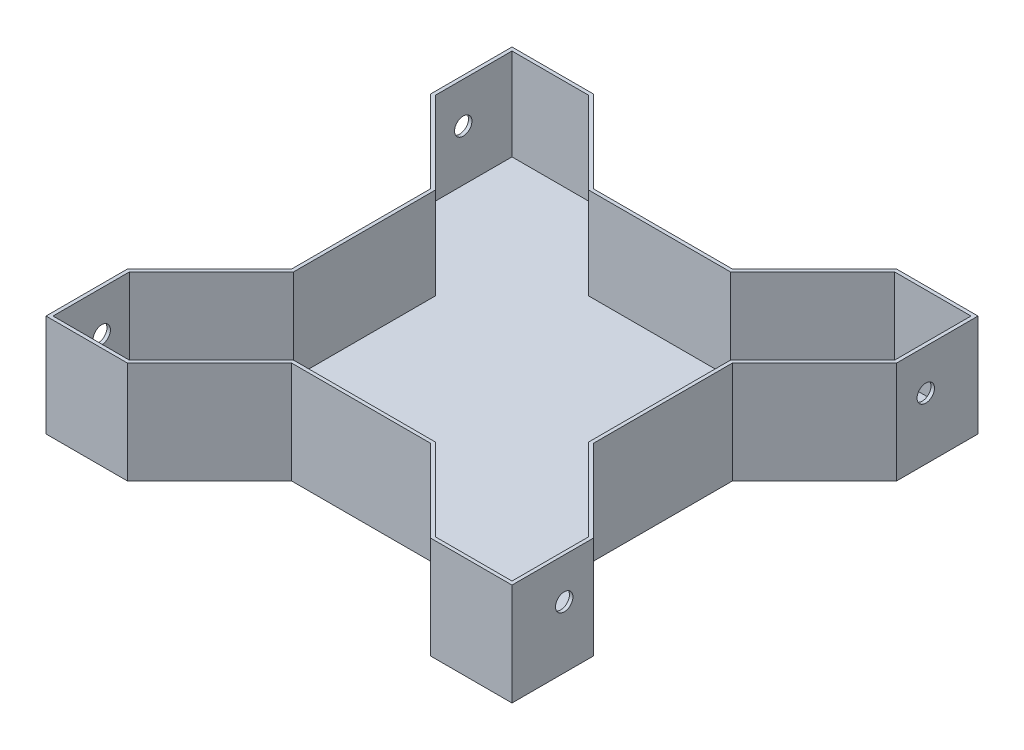
SolidWorks part; units mm, degrees
other "Markup1"
sketch "Sketch24" plane through (-161.6422, 88, 252.2031) normal (-0.9961, 0.087, 0.0135) x (-0.0555, -0.7403, 0.6699)
material "1023 Carbon Steel Sheet (SS)"
ref_plane "Front Plane" through (0, 0, 0) normal (0, 0, 1) x (1, 0, 0)
ref_plane "Top Plane" through (0, 0, 0) normal (0, 1, 0) x (1, 0, 0)
ref_plane "Right Plane" through (0, 0, 0) normal (1, 0, 0) x (0, 0, -1)
sketch "Sketch1" plane through (0, 0, 0) normal (0, 1, 0) x (1, 0, 0)
  line L0 (-161.6422, 149.2183) -> (-91.6422, 149.2183)
  line L1 (-91.6422, 149.2183) -> (-20.9315, 78.5076)
  line L2 (-20.9315, 78.5076) -> (99.0685, 78.5076)
  line L3 (99.0685, 78.5076) -> (169.7792, 149.2183)
  line L4 (169.7792, 149.2183) -> (239.7792, 149.2183)
  line L5 (239.7792, 149.2183) -> (239.7792, 79.2183)
  line L6 (239.7792, 79.2183) -> (169.0685, 8.5076)
  line L7 (169.0685, 8.5076) -> (169.0685, -111.4924)
  line L8 (169.0685, -111.4924) -> (239.7792, -182.2031)
  line L9 (239.7792, -182.2031) -> (239.7792, -252.2031)
  line L10 (239.7792, -252.2031) -> (169.7792, -252.2031)
  line L11 (169.7792, -252.2031) -> (99.0685, -181.4924)
  line L12 (99.0685, -181.4924) -> (-20.9315, -181.4924)
  line L13 (-20.9315, -181.4924) -> (-91.6422, -252.2031)
  line L14 (-91.6422, -252.2031) -> (-161.6422, -252.2031)
  line L15 (-161.6422, -252.2031) -> (-161.6422, -182.2031)
  line L16 (-161.6422, -182.2031) -> (-90.9315, -111.4924)
  line L17 (-90.9315, -111.4924) -> (-90.9315, 8.5076)
  line L18 (-90.9315, 8.5076) -> (-161.6422, 79.2183)
  line L19 (-161.6422, 79.2183) -> (-161.6422, 149.2183)
  dimension "D1" = 70
  dimension "D2" = 70
  dimension "D3" = 70
  dimension "D4" = 70
  dimension "D5" = 70
  dimension "D6" = 70
  dimension "D7" = 70
  dimension "D8" = 70
  dimension "D9" = 100
  dimension "D10" = 100
  dimension "D11" = 100
  dimension "D12" = 100
  dimension "D13" = 100
  dimension "D14" = 100
  dimension "D15" = 100
  dimension "D16" = 100
  dimension "D17" = 135
  dimension "D18" = 120
  dimension "D19" = 120
  dimension "D20" = 135
  dimension "D21" = 135
  dimension "D22" = 135
  dimension "D23" = 135
extrude "Boss-Extrude1" add sketch "Sketch1" along normal blind 88 contours L1 L2 L3 L4 L5 L6 L7 L8 L9 L10 L11 L12 L13 L14 L15 L16 L17 L18 L19 L0
sketch "Sketch3" plane through (0, 88, 0) normal (0, 1, 0) x (1, 0, 0)
  line L0 (-161.6422, 79.2183) -> (-161.6422, 149.2183) construction
  line L1 (-161.6422, 149.2183) -> (-91.6422, 149.2183) construction
  line L2 (-91.6422, 149.2183) -> (-20.9315, 78.5076) construction
  line L3 (239.7792, 149.2183) -> (239.7792, 79.2183) construction
  line L4 (-90.9315, 8.5076) -> (-161.6422, 79.2183) construction
  line L5 (169.7792, 149.2183) -> (239.7792, 149.2183) construction
  line L6 (-20.9315, 78.5076) -> (99.0685, 78.5076) construction
  line L7 (-90.9315, -111.4924) -> (-90.9315, 8.5076) construction
  line L8 (99.0685, 78.5076) -> (169.7792, 149.2183) construction
  line L9 (-158.6422, 146.2183) -> (-158.6422, 80.4609)
  line L10 (171.0218, 146.2183) -> (100.3112, 75.5076)
  line L11 (-158.6422, 80.4609) -> (-87.9315, 9.7503)
  line L12 (-87.9315, 9.7503) -> (-87.9315, -112.735)
  line L13 (-87.9315, -112.735) -> (-158.6422, -183.4457)
  line L14 (-158.6422, -183.4457) -> (-158.6422, -249.2031)
  line L15 (-158.6422, -249.2031) -> (-92.8848, -249.2031)
  line L16 (-92.8848, -249.2031) -> (-22.1741, -178.4924)
  line L17 (-22.1741, -178.4924) -> (100.3112, -178.4924)
  line L18 (100.3112, -178.4924) -> (171.0218, -249.2031)
  line L19 (171.0218, -249.2031) -> (236.7792, -249.2031)
  line L20 (236.7792, -249.2031) -> (236.7792, -183.4457)
  line L21 (236.7792, -183.4457) -> (166.0685, -112.735)
  line L22 (166.0685, -112.735) -> (166.0685, 9.7503)
  line L23 (166.0685, 9.7503) -> (236.7792, 80.4609)
  line L24 (236.7792, 80.4609) -> (236.7792, 146.2183)
  line L25 (236.7792, 146.2183) -> (171.0218, 146.2183)
  line L26 (100.3112, 75.5076) -> (-22.1741, 75.5076)
  line L27 (-22.1741, 75.5076) -> (-92.8848, 146.2183)
  line L28 (-92.8848, 146.2183) -> (-158.6422, 146.2183)
  point P0 (-158.6422, 146.2183)
  point P5 (-158.6422, 80.4609)
  point P6 (-87.9315, 9.7503)
  point P10 (236.7792, 146.2183)
  point P11 (171.0218, 146.2183)
  point P12 (100.3112, 75.5076)
  point P18 (166.0685, 9.7503)
  point P19 (236.7792, 80.4609)
  point P20 (166.0685, -112.735)
  point P21 (236.7792, -183.4457)
  point P22 (-22.1741, 75.5076)
  point P23 (-92.8848, 146.2183)
  point P26 (236.7792, -249.2031)
  point P28 (171.0218, -249.2031)
  point P30 (100.3112, -178.4924)
  point P32 (-92.8848, -249.2031)
  point P37 (-22.1741, -178.4924)
  point P38 (-87.9315, -112.735)
  point P39 (-158.6422, -183.4457)
  point P40 (-158.6422, -249.2031)
  dimension "D1" = 3
  dimension "D2" = 3
  dimension "D3" = 3
  dimension "D4" = 3
  dimension "D5" = 3
  dimension "D6" = 3
  dimension "D7" = 3
  dimension "D8" = 3
  dimension "D9" = 3
  dimension "D10" = 3
  dimension "D11" = 3
  dimension "D12" = 3
  dimension "D13" = 3
  dimension "D14" = 3
  dimension "D15" = 3
  dimension "D16" = 3
extrude "Cut-Extrude1" cut sketch "Sketch3" against normal blind 79
sketch "Sketch4" plane through (239.7792, 0, 0) normal (1, 0, 0) x (0, 0, -1)
  line L0 (-182.2031, 88) -> (-252.2031, 88) construction
  line L1 (-252.2031, 88) -> (-252.2031, 0) construction
  circle A0 centre (-207.2031, 53) radius 7.5
  dimension "D1" = 35
  dimension "D2" = 45
extrude "Cut-Extrude2" cut sketch "Sketch4" against normal blind 47
sketch "Sketch6" plane through (239.7792, 0, 0) normal (1, 0, 0) x (0, 0, -1)
  line L0 (149.2183, 88) -> (79.2183, 88) construction
  line L1 (149.2183, 88) -> (149.2183, 0) construction
  circle A0 centre (104.2183, 53) radius 7.5
  dimension "D1" = 35
  dimension "D2" = 45
extrude "Cut-Extrude4" cut sketch "Sketch6" against normal blind 47
sketch "Sketch7" plane through (-161.6422, 0, 0) normal (-1, 0, 0) x (0, 0, 1)
  line L2 (-79.2183, 0) -> (-149.2183, 0) construction
  line L3 (-149.2183, 88) -> (-149.2183, 0) construction
  circle A0 centre (-104.2183, 53) radius 7.5
  dimension "D1" = 53
  dimension "D2" = 45
extrude "Cut-Extrude5" cut sketch "Sketch7" against normal blind 47
sketch "Sketch8" plane through (-161.6422, 0, 0) normal (-1, 0, 0) x (0, 0, 1)
  line L2 (252.2031, 88) -> (182.2031, 88) construction
  line L3 (252.2031, 88) -> (252.2031, 0) construction
  circle A0 centre (207.2031, 53) radius 7.5
  dimension "D1" = 35
  dimension "D2" = 45
extrude "Cut-Extrude6" cut sketch "Sketch8" against normal blind 47
sketch "Sketch10" plane through (0, 9, 0) normal (0, 1, 0) x (1, 0, 0)
  line L0 (-158.6422, 126.2183) -> (-158.6422, 100.4609)
  line L1 (-158.6422, 126.2183) -> (-161.6422, 126.2183)
  line L2 (-161.6422, 126.2183) -> (-161.6422, 136.2183)
  line L3 (-158.6422, 136.2183) -> (-161.6422, 136.2183)
  line L4 (-158.6422, 90.4609) -> (-161.6422, 90.4609)
  line L5 (-161.6422, 100.4609) -> (-161.6422, 90.4609)
  line L6 (-158.6422, 100.4609) -> (-161.6422, 100.4609)
  line L7 (-158.6422, 90.4609) -> (-158.6422, 80.4609)
  line L8 (-20.9315, 78.5076) -> (99.0685, 78.5076) construction
  line L9 (181.0218, 146.2183) -> (181.0218, 149.2183)
  line L10 (191.0218, 149.2183) -> (181.0218, 149.2183)
  line L11 (191.0218, 146.2183) -> (191.0218, 149.2183)
  line L12 (236.7792, 90.4609) -> (239.7792, 90.4609)
  line L13 (239.7792, 100.4609) -> (239.7792, 90.4609)
  line L14 (236.7792, 100.4609) -> (239.7792, 100.4609)
  line L15 (236.7792, 126.2183) -> (239.7792, 126.2183)
  line L16 (239.7792, 126.2183) -> (239.7792, 136.2183)
  line L17 (236.7792, 136.2183) -> (239.7792, 136.2183)
  line L18 (216.7792, 146.2183) -> (216.7792, 149.2183)
  line L19 (226.7792, 146.2183) -> (226.7792, 149.2183)
  line L20 (216.7792, 149.2183) -> (226.7792, 149.2183)
  line L22 (-112.8848, 146.2183) -> (-112.8848, 149.2183)
  line L23 (-112.8848, 149.2183) -> (-102.8848, 149.2183)
  line L24 (-102.8848, 146.2183) -> (-102.8848, 149.2183)
  line L25 (-112.8848, 146.2183) -> (-138.6422, 146.2183)
  line L26 (-148.6422, 146.2183) -> (-148.6422, 149.2183)
  line L27 (-138.6422, 146.2183) -> (-138.6422, 149.2183)
  line L28 (-138.6422, 149.2183) -> (-148.6422, 149.2183)
  line L29 (-148.6422, 146.2183) -> (-158.6422, 146.2183)
  line L30 (-12.1741, 75.5076) -> (-12.1741, 78.5076)
  line L31 (-12.1741, 78.5076) -> (-2.1741, 78.5076)
  line L32 (-2.1741, 78.5076) -> (-2.1741, 75.5076)
  line L33 (39.0685, 78.5076) -> (39.0685, 67.3065) construction
  line L34 (80.3112, 78.5076) -> (80.3112, 75.5076)
  line L35 (90.3112, 78.5076) -> (80.3112, 78.5076)
  line L36 (90.3112, 75.5076) -> (90.3112, 78.5076)
  line L37 (-91.6422, 149.2183) -> (-20.9315, 78.5076) construction
  line L38 (-92.8848, 146.2183) -> (-86.7925, 152.3106) construction
  line L39 (-83.6924, 141.2686) -> (-85.8137, 139.1472)
  line L40 (-92.8848, 146.2183) -> (-158.6422, 146.2183)
  line L41 (-158.6422, 146.2183) -> (-158.6422, 80.4609)
  line L42 (-158.6422, 80.4609) -> (-87.9315, 9.7503)
  line L43 (-87.9315, 9.7503) -> (-87.9315, -112.735)
  line L44 (-87.9315, -112.735) -> (-158.6422, -183.4457)
  line L45 (-158.6422, -183.4457) -> (-158.6422, -249.2031)
  line L46 (-158.6422, -249.2031) -> (-92.8848, -249.2031)
  line L47 (-92.8848, -249.2031) -> (-22.1741, -178.4924)
  line L48 (-22.1741, -178.4924) -> (100.3112, -178.4924)
  line L49 (100.3112, -178.4924) -> (171.0218, -249.2031)
  line L50 (171.0218, -249.2031) -> (236.7792, -249.2031)
  line L51 (236.7792, -249.2031) -> (236.7792, -183.4457)
  line L52 (236.7792, -183.4457) -> (166.0685, -112.735)
  line L53 (166.0685, -112.735) -> (166.0685, 9.7503)
  line L54 (166.0685, 9.7503) -> (236.7792, 80.4609)
  line L55 (236.7792, 80.4609) -> (236.7792, 146.2183)
  line L56 (236.7792, 146.2183) -> (171.0218, 146.2183)
  line L57 (171.0218, 146.2183) -> (100.3112, 75.5076)
  line L58 (100.3112, 75.5076) -> (-22.1741, 75.5076)
  line L59 (-22.1741, 75.5076) -> (-92.8848, 146.2183)
  line L60 (-92.8848, 146.2183) -> (-102.8848, 146.2183)
  line L61 (-158.6422, 146.2183) -> (-158.6422, 136.2183)
  line L62 (-158.6422, 80.4609) -> (-151.5711, 73.3899)
  line L63 (-87.9315, 9.7503) -> (-87.9315, -0.2497)
  line L64 (-87.9315, -112.735) -> (-95.0026, -119.8061)
  line L65 (-158.6422, -183.4457) -> (-158.6422, -193.4457)
  line L66 (-158.6422, -249.2031) -> (-148.6422, -249.2031)
  line L67 (-92.8848, -249.2031) -> (-85.8137, -242.132)
  line L68 (-22.1741, -178.4924) -> (-12.1741, -178.4924)
  line L69 (100.3112, -178.4924) -> (107.3822, -185.5634)
  line L70 (171.0218, -249.2031) -> (181.0218, -249.2031)
  line L71 (236.7792, -249.2031) -> (236.7792, -239.2031)
  line L72 (236.7792, -183.4457) -> (229.7081, -176.3746)
  line L73 (166.0685, -112.735) -> (166.0685, -102.735)
  line L74 (166.0685, 9.7503) -> (173.1396, 16.8213)
  line L75 (236.7792, 80.4609) -> (236.7792, 90.4609)
  line L76 (236.7792, 146.2183) -> (226.7792, 146.2183)
  line L77 (171.0218, 146.2183) -> (163.9508, 139.1472)
  line L78 (100.3112, 75.5076) -> (90.3112, 75.5076)
  line L79 (-22.1741, 75.5076) -> (-29.2452, 82.5787)
  line L80 (-83.6924, 141.2686) -> (-76.6213, 134.1975)
  line L81 (-76.6213, 134.1975) -> (-78.7427, 132.0762)
  line L82 (105.2609, 84.7) -> (107.3822, 82.5787)
  line L83 (-34.1949, 91.7711) -> (-36.3163, 89.6498)
  line L84 (-27.1239, 84.7) -> (-34.1949, 91.7711)
  line L85 (-27.1239, 84.7) -> (-29.2452, 82.5787)
  line L86 (105.2609, 84.7) -> (112.332, 91.7711)
  line L87 (112.332, 91.7711) -> (114.4533, 89.6498)
  line L88 (161.8294, 141.2686) -> (163.9508, 139.1472)
  line L89 (161.8294, 141.2686) -> (154.7584, 134.1975)
  line L90 (154.7584, 134.1975) -> (156.8797, 132.0762)
  line L91 (-161.6422, 149.2183) -> (-158.6422, 146.2183) construction
  line L92 (-97.1239, 14.7) -> (-95.0026, 16.8213)
  line L93 (-97.1239, 14.7) -> (-104.1949, 21.7711)
  line L94 (-104.1949, 21.7711) -> (-102.0736, 23.8924)
  line L95 (-146.6213, 64.1975) -> (-144.5, 66.3188)
  line L96 (-153.6924, 71.2686) -> (-146.6213, 64.1975)
  line L97 (-153.6924, 71.2686) -> (-151.5711, 73.3899)
  line L98 (239.7792, 149.2183) -> (236.7792, 146.2183) construction
  line L99 (182.332, 21.7711) -> (180.2106, 23.8924)
  line L100 (175.2609, 14.7) -> (182.332, 21.7711)
  line L101 (175.2609, 14.7) -> (173.1396, 16.8213)
  line L102 (224.7584, 64.1975) -> (222.6371, 66.3188)
  line L103 (231.8294, 71.2686) -> (229.7081, 73.3899)
  line L104 (231.8294, 71.2686) -> (224.7584, 64.1975)
  line L105 (-90.9315, -111.4924) -> (-90.9315, 8.5076) construction
  line L106 (-87.9315, -0.2497) -> (-90.9315, -0.2497)
  line L107 (-90.9315, -0.2497) -> (-90.9315, -10.2497)
  line L108 (-90.9315, -10.2497) -> (-87.9315, -10.2497)
  line L109 (169.0685, -10.2497) -> (166.0685, -10.2497)
  line L110 (166.0685, -0.2497) -> (169.0685, -0.2497)
  line L111 (169.0685, -0.2497) -> (169.0685, -10.2497)
  line L112 (-87.9315, -10.2497) -> (-87.9315, -92.735)
  line L113 (-95.0026, 16.8213) -> (-87.9315, 9.7503)
  line L114 (-144.5, 66.3188) -> (-102.0736, 23.8924)
  line L115 (-85.8137, 139.1472) -> (-92.8848, 146.2183)
  line L116 (-36.3163, 89.6498) -> (-78.7427, 132.0762)
  line L117 (-12.1741, 75.5076) -> (-22.1741, 75.5076)
  line L118 (80.3112, 75.5076) -> (-2.1741, 75.5076)
  line L119 (107.3822, 82.5787) -> (100.3112, 75.5076)
  line L120 (156.8797, 132.0762) -> (114.4533, 89.6498)
  line L121 (181.0218, 146.2183) -> (171.0218, 146.2183)
  line L122 (216.7792, 146.2183) -> (191.0218, 146.2183)
  line L123 (236.7792, 136.2183) -> (236.7792, 146.2183)
  line L124 (236.7792, 100.4609) -> (236.7792, 126.2183)
  line L125 (229.7081, 73.3899) -> (236.7792, 80.4609)
  line L126 (180.2106, 23.8924) -> (222.6371, 66.3188)
  line L127 (166.0685, -0.2497) -> (166.0685, 9.7503)
  line L128 (-90.9315, -51.4924) -> (224.7584, -51.4924) construction
  line L129 (166.0685, -92.735) -> (166.0685, -10.2497)
  line L130 (-83.6924, 141.2686) -> (-85.8137, 139.1472)
  line L131 (-83.6924, 141.2686) -> (-76.6213, 134.1975)
  line L132 (-76.6213, 134.1975) -> (-78.7427, 132.0762)
  line L133 (-161.6422, 126.2183) -> (-161.6422, 136.2183)
  line L134 (-158.6422, 126.2183) -> (-161.6422, 126.2183)
  line L135 (-158.6422, 136.2183) -> (-161.6422, 136.2183)
  line L136 (-112.8848, 146.2183) -> (-112.8848, 149.2183)
  line L137 (-76.6213, -237.1822) -> (-78.7427, -235.0609)
  line L138 (-83.6924, -244.2533) -> (-76.6213, -237.1822)
  line L139 (-83.6924, -244.2533) -> (-85.8137, -242.132)
  line L140 (-102.8848, -249.2031) -> (-102.8848, -252.2031)
  line L141 (-112.8848, -252.2031) -> (-102.8848, -252.2031)
  line L142 (-112.8848, -249.2031) -> (-112.8848, -252.2031)
  line L143 (-112.8848, 149.2183) -> (-102.8848, 149.2183)
  line L144 (-102.8848, 146.2183) -> (-102.8848, 149.2183)
  line L145 (-148.6422, 146.2183) -> (-148.6422, 149.2183)
  line L146 (-138.6422, 149.2183) -> (-148.6422, 149.2183)
  line L147 (-138.6422, 146.2183) -> (-138.6422, 149.2183)
  line L148 (-158.6422, 126.2183) -> (-161.6422, 126.2183)
  line L149 (-161.6422, 126.2183) -> (-161.6422, 136.2183)
  line L150 (-158.6422, 136.2183) -> (-161.6422, 136.2183)
  line L151 (-148.6422, 146.2183) -> (-148.6422, 149.2183)
  line L152 (-138.6422, 146.2183) -> (-138.6422, 149.2183)
  line L153 (-138.6422, 149.2183) -> (-148.6422, 149.2183)
  line L154 (-83.6924, 141.2686) -> (-85.8137, 139.1472)
  line L155 (-83.6924, 141.2686) -> (-76.6213, 134.1975)
  line L156 (-76.6213, 134.1975) -> (-78.7427, 132.0762)
  line L157 (-161.6422, 126.2183) -> (-161.6422, 136.2183)
  line L158 (-158.6422, 126.2183) -> (-161.6422, 126.2183)
  line L159 (-158.6422, 136.2183) -> (-161.6422, 136.2183)
  line L160 (-112.8848, 146.2183) -> (-112.8848, 149.2183)
  line L161 (-112.8848, 149.2183) -> (-102.8848, 149.2183)
  line L162 (-102.8848, 146.2183) -> (-102.8848, 149.2183)
  line L163 (-148.6422, 146.2183) -> (-148.6422, 149.2183)
  line L164 (-138.6422, 149.2183) -> (-148.6422, 149.2183)
  line L165 (-138.6422, 146.2183) -> (-138.6422, 149.2183)
  line L166 (-148.6422, -249.2031) -> (-148.6422, -252.2031)
  line L167 (-138.6422, -249.2031) -> (-138.6422, -252.2031)
  line L168 (-138.6422, -252.2031) -> (-148.6422, -252.2031)
  line L169 (-158.6422, -239.2031) -> (-161.6422, -239.2031)
  line L170 (-158.6422, -229.2031) -> (-161.6422, -229.2031)
  line L171 (-161.6422, -229.2031) -> (-161.6422, -239.2031)
  line L172 (-158.6422, -239.2031) -> (-161.6422, -239.2031)
  line L173 (-161.6422, -229.2031) -> (-161.6422, -239.2031)
  line L174 (-158.6422, -229.2031) -> (-161.6422, -229.2031)
  line L175 (-158.6422, -239.2031) -> (-161.6422, -239.2031)
  line L176 (-158.6422, -229.2031) -> (-161.6422, -229.2031)
  line L177 (-161.6422, -229.2031) -> (-161.6422, -239.2031)
  line L178 (-153.6924, -174.2533) -> (-151.5711, -176.3746)
  line L179 (-153.6924, -174.2533) -> (-146.6213, -167.1822)
  line L180 (-146.6213, -167.1822) -> (-144.5, -169.3036)
  line L181 (-158.6422, -203.4457) -> (-161.6422, -203.4457)
  line L182 (-161.6422, -203.4457) -> (-161.6422, -193.4457)
  line L183 (-158.6422, -193.4457) -> (-161.6422, -193.4457)
  line L184 (-158.6422, -239.2031) -> (-161.6422, -239.2031)
  line L185 (-161.6422, -229.2031) -> (-161.6422, -239.2031)
  line L186 (-158.6422, -229.2031) -> (-161.6422, -229.2031)
  line L187 (-90.9315, -92.735) -> (-87.9315, -92.735)
  line L188 (-90.9315, -102.735) -> (-90.9315, -92.735)
  line L189 (-87.9315, -102.735) -> (-90.9315, -102.735)
  line L190 (-97.1239, -117.6848) -> (-95.0026, -119.8061)
  line L191 (-97.1239, -117.6848) -> (-104.1949, -124.7558)
  line L192 (-12.1741, -178.4924) -> (-12.1741, -181.4924)
  line L193 (-12.1741, -181.4924) -> (-2.1741, -181.4924)
  line L194 (239.7792, -252.2031) -> (236.7792, -249.2031) construction
  line L195 (39.0685, -181.4924) -> (39.0685, -170.2913) construction
  line L196 (169.0685, -102.735) -> (169.0685, -92.735)
  line L197 (166.0685, -102.735) -> (169.0685, -102.735)
  line L198 (169.0685, -92.735) -> (166.0685, -92.735)
  line L199 (231.8294, -174.2533) -> (224.7584, -167.1822)
  line L200 (231.8294, -174.2533) -> (229.7081, -176.3746)
  line L201 (224.7584, -167.1822) -> (222.6371, -169.3036)
  line L202 (175.2609, -117.6848) -> (173.1396, -119.8061)
  line L203 (175.2609, -117.6848) -> (182.332, -124.7558)
  line L204 (182.332, -124.7558) -> (180.2106, -126.8771)
  line L205 (154.7584, -237.1822) -> (156.8797, -235.0609)
  line L206 (161.8294, -244.2533) -> (154.7584, -237.1822)
  line L207 (161.8294, -244.2533) -> (163.9508, -242.132)
  line L208 (112.332, -194.7558) -> (114.4533, -192.6345)
  line L209 (105.2609, -187.6848) -> (112.332, -194.7558)
  line L210 (105.2609, -187.6848) -> (107.3822, -185.5634)
  line L211 (90.3112, -178.4924) -> (90.3112, -181.4924)
  line L212 (90.3112, -181.4924) -> (80.3112, -181.4924)
  line L213 (80.3112, -181.4924) -> (80.3112, -178.4924)
  line L214 (-2.1741, -181.4924) -> (-2.1741, -178.4924)
  line L215 (216.7792, -252.2031) -> (226.7792, -252.2031)
  line L216 (226.7792, -249.2031) -> (226.7792, -252.2031)
  line L217 (216.7792, -249.2031) -> (216.7792, -252.2031)
  line L218 (236.7792, -239.2031) -> (239.7792, -239.2031)
  line L219 (239.7792, -229.2031) -> (239.7792, -239.2031)
  line L220 (236.7792, -229.2031) -> (239.7792, -229.2031)
  line L221 (236.7792, -203.4457) -> (239.7792, -203.4457)
  line L222 (239.7792, -203.4457) -> (239.7792, -193.4457)
  line L223 (236.7792, -193.4457) -> (239.7792, -193.4457)
  line L224 (191.0218, -249.2031) -> (191.0218, -252.2031)
  line L225 (191.0218, -252.2031) -> (181.0218, -252.2031)
  line L226 (181.0218, -249.2031) -> (181.0218, -252.2031)
  line L227 (-87.9315, -102.735) -> (-87.9315, -112.735)
  line L228 (-151.5711, -176.3746) -> (-158.6422, -183.4457)
  line L229 (-158.6422, -203.4457) -> (-158.6422, -249.2031)
  line L230 (-138.6422, -249.2031) -> (-112.8848, -249.2031)
  line L231 (-102.8848, -249.2031) -> (-92.8848, -249.2031)
  line L232 (-78.7427, -235.0609) -> (-22.1741, -178.4924)
  line L233 (-2.1741, -178.4924) -> (80.3112, -178.4924)
  line L234 (90.3112, -178.4924) -> (100.3112, -178.4924)
  line L235 (114.4533, -192.6345) -> (156.8797, -235.0609)
  line L236 (163.9508, -242.132) -> (171.0218, -249.2031)
  line L237 (191.0218, -249.2031) -> (216.7792, -249.2031)
  line L238 (226.7792, -249.2031) -> (236.7792, -249.2031)
  line L239 (236.7792, -229.2031) -> (236.7792, -203.4457)
  line L240 (236.7792, -193.4457) -> (236.7792, -183.4457)
  line L241 (222.6371, -169.3036) -> (180.2106, -126.8771)
  line L242 (173.1396, -119.8061) -> (166.0685, -112.735)
  line L243 (-104.1949, -124.7558) -> (-102.0736, -126.8771)
  line L244 (-102.0736, -126.8771) -> (-144.5, -169.3036)
  point P7 (-12.1741, 78.5076)
  point P48 (226.7792, 147.7183)
  point P68 (-83.6924, 141.2686)
  point P107 (-90.9315, -0.2497)
  point P150 (-102.0736, -126.8771)
  point P199 (226.7792, -250.7031)
  dimension "D2" = 3
  dimension "D3" = 10
  dimension "D4" = 10
  dimension "D5" = 10
  dimension "D6" = 10
  dimension "D7" = 10
  dimension "D8" = 10
  dimension "D9" = 10
  dimension "D10" = 10
  dimension "D1" = 0
sketch "Sketch11" plane through (0, 0, -78.5076) normal (0, 0, -1) x (-1, 0, 0)
  line L0 (-90.3112, 9) -> (-90.3112, 10.5)
  line L1 (-90.3112, 9) -> (-100.3112, 9) construction
  line L2 (-90.3112, 10.5) -> (-80.3112, 10.5)
  line L3 (-80.3112, 10.5) -> (-80.3112, 9)
  line L4 (-99.0685, 0) -> (20.9315, 0)
  line L5 (20.9315, 0) -> (20.9315, 88)
  line L6 (20.9315, 88) -> (-99.0685, 88)
  line L7 (-99.0685, 88) -> (-99.0685, 0)
  line L8 (-99.0685, 0) -> (20.9315, 0)
  line L9 (20.9315, 0) -> (20.9315, 88)
  line L10 (20.9315, 88) -> (-99.0685, 88)
  line L11 (-99.0685, 88) -> (-99.0685, 0)
  line L12 (2.1741, 9) -> (-80.3112, 9) construction
  line L13 (-80.3112, 9) -> (-80.3112, 7.5)
  line L14 (-80.3112, 7.5) -> (-90.3112, 7.5)
  line L15 (-90.3112, 7.5) -> (-90.3112, 9)
  line L16 (-39.0685, 9) -> (-39.0685, 30.0924) construction
  line L17 (12.1741, 7.5) -> (12.1741, 9)
  line L18 (2.1741, 7.5) -> (12.1741, 7.5)
  line L19 (2.1741, 9) -> (2.1741, 7.5)
  line L20 (2.1741, 10.5) -> (2.1741, 9)
  line L21 (12.1741, 10.5) -> (2.1741, 10.5)
  line L22 (12.1741, 9) -> (12.1741, 10.5)
  dimension "D2" = 10
  dimension "D3" = 10
  dimension "D4" = 1.5
  dimension "D5" = 1.5
  dimension "D1" = 0
sketch "Sketch12" plane through (10.2804, 0, 10.2804) normal (-0.7071, 0, -0.7071) x (-0.7071, 0, 0.7071)
  line L0 (-214.3227, 9) -> (-214.3227, 10.5)
  line L1 (-214.3227, 9) -> (-204.3227, 9) construction
  line L2 (-214.3227, 9) -> (-224.3227, 9) construction
  line L3 (-214.3227, 10.5) -> (-204.3227, 10.5)
  line L4 (-225.5653, 0) -> (-125.5653, 0)
  line L5 (-125.5653, 0) -> (-125.5653, 88)
  line L6 (-125.5653, 88) -> (-225.5653, 88)
  line L7 (-225.5653, 88) -> (-225.5653, 0)
  line L8 (-225.5653, 0) -> (-125.5653, 0)
  line L9 (-125.5653, 0) -> (-125.5653, 88)
  line L10 (-125.5653, 88) -> (-225.5653, 88)
  line L11 (-225.5653, 88) -> (-225.5653, 0)
  line L12 (-204.3227, 10.5) -> (-204.3227, 9)
  line L13 (-204.3227, 9) -> (-204.3227, 7.5)
  line L14 (-204.3227, 7.5) -> (-214.3227, 7.5)
  line L15 (-214.3227, 7.5) -> (-214.3227, 9)
  line L16 (-174.3227, 9) -> (-174.3227, 17.0419) construction
  line L17 (-144.3227, 9) -> (-204.3227, 9) construction
  line L18 (-134.3227, 7.5) -> (-134.3227, 9)
  line L19 (-144.3227, 7.5) -> (-134.3227, 7.5)
  line L20 (-144.3227, 9) -> (-144.3227, 7.5)
  line L21 (-144.3227, 10.5) -> (-144.3227, 9)
  line L22 (-134.3227, 10.5) -> (-144.3227, 10.5)
  line L23 (-134.3227, 9) -> (-134.3227, 10.5)
  dimension "D2" = 10
  dimension "D3" = 1.5
  dimension "D4" = 1.5
  dimension "D1" = 0
sketch "Sketch13" plane through (0, 0, -149.2183) normal (0, 0, -1) x (-1, 0, 0)
  line L0 (-226.7792, 9) -> (-226.7792, 10.5)
  line L1 (-226.7792, 10.5) -> (-216.7792, 10.5)
  line L2 (-216.7792, 10.5) -> (-216.7792, 9)
  line L3 (-216.7792, 9) -> (-216.7792, 7.5)
  line L4 (-239.7792, 0) -> (-169.7792, 0)
  line L5 (-169.7792, 0) -> (-169.7792, 88)
  line L6 (-169.7792, 88) -> (-239.7792, 88)
  line L7 (-239.7792, 88) -> (-239.7792, 0)
  line L8 (-239.7792, 0) -> (-169.7792, 0)
  line L9 (-169.7792, 0) -> (-169.7792, 88)
  line L10 (-169.7792, 88) -> (-239.7792, 88)
  line L11 (-239.7792, 88) -> (-239.7792, 0)
  line L12 (-216.7792, 7.5) -> (-226.7792, 7.5)
  line L13 (-226.7792, 7.5) -> (-226.7792, 9)
  line L14 (-201.4239, 9) -> (-201.4239, 19.1162) construction
  line L15 (-222.6371, 9) -> (-180.2106, 9) construction
  line L16 (-191.0218, 9) -> (-191.0218, 10.5)
  line L17 (-191.0218, 10.5) -> (-181.0218, 10.5)
  line L18 (-181.0218, 10.5) -> (-181.0218, 9)
  line L19 (-181.0218, 9) -> (-181.0218, 7.5)
  line L20 (-181.0218, 7.5) -> (-191.0218, 7.5)
  line L21 (-191.0218, 7.5) -> (-191.0218, 9)
  dimension "D2" = 10
  dimension "D3" = 1.5
  dimension "D4" = 1.5
  dimension "D5" = 10
  dimension "D6" = 1.5
  dimension "D7" = 1.5
  dimension "D1" = 0
sketch "Sketch14" plane through (239.7792, 0, 0) normal (1, 0, 0) x (0, 0, -1)
  line L0 (100.4609, 9) -> (100.4609, 7.5)
  line L1 (100.4609, 7.5) -> (90.222, 7.5)
  line L2 (90.222, 7.5) -> (90.4609, 9)
  line L3 (90.4609, 9) -> (90.4609, 10.5)
  line L4 (79.2183, 0) -> (149.2183, 0)
  line L5 (149.2183, 0) -> (149.2183, 88)
  line L6 (149.2183, 88) -> (79.2183, 88)
  line L7 (79.2183, 88) -> (79.2183, 0)
  line L8 (79.2183, 0) -> (149.2183, 0)
  line L9 (149.2183, 0) -> (149.2183, 88)
  line L10 (149.2183, 88) -> (79.2183, 88)
  line L11 (79.2183, 88) -> (79.2183, 0)
  line L12 (90.4609, 10.5) -> (100.4609, 10.5)
  line L13 (100.4609, 10.5) -> (100.4609, 9)
  line L14 (126.2183, 9) -> (126.2183, 10.5)
  line L15 (126.2183, 10.5) -> (136.2183, 10.5)
  line L16 (136.2183, 10.5) -> (136.2183, 9)
  line L17 (136.2183, 9) -> (136.2183, 7.5)
  line L18 (136.2183, 7.5) -> (126.2183, 7.5)
  line L19 (126.2183, 7.5) -> (126.2183, 9)
  dimension "D2" = 1.5
  dimension "D3" = 1.5
  dimension "D4" = 10
  dimension "D5" = 1.5
  dimension "D6" = 1.5
  dimension "D1" = 0
sketch "Sketch16" plane through (0, 9, 0) normal (0, 1, 0) x (1, 0, 0)
  line L20 (-92.8848, 146.2183) -> (-158.6422, 146.2183)
  line L21 (-158.6422, 146.2183) -> (-158.6422, 80.4609)
  line L22 (-158.6422, 80.4609) -> (-87.9315, 9.7503)
  line L23 (-87.9315, 9.7503) -> (-87.9315, -112.735)
  line L24 (-87.9315, -112.735) -> (-158.6422, -183.4457)
  line L25 (-158.6422, -183.4457) -> (-158.6422, -249.2031)
  line L26 (-158.6422, -249.2031) -> (-92.8848, -249.2031)
  line L27 (-92.8848, -249.2031) -> (-22.1741, -178.4924)
  line L28 (-22.1741, -178.4924) -> (100.3112, -178.4924)
  line L29 (100.3112, -178.4924) -> (171.0218, -249.2031)
  line L30 (171.0218, -249.2031) -> (236.7792, -249.2031)
  line L31 (236.7792, -249.2031) -> (236.7792, -183.4457)
  line L32 (236.7792, -183.4457) -> (166.0685, -112.735)
  line L33 (166.0685, -112.735) -> (166.0685, 9.7503)
  line L34 (166.0685, 9.7503) -> (236.7792, 80.4609)
  line L35 (236.7792, 80.4609) -> (236.7792, 146.2183)
  line L36 (236.7792, 146.2183) -> (171.0218, 146.2183)
  line L37 (171.0218, 146.2183) -> (100.3112, 75.5076)
  line L38 (100.3112, 75.5076) -> (-22.1741, 75.5076)
  line L39 (-22.1741, 75.5076) -> (-92.8848, 146.2183)
  line L40 (-92.8848, 146.2183) -> (-158.6422, 146.2183)
  line L41 (-158.6422, 146.2183) -> (-158.6422, 80.4609)
  line L42 (-158.6422, 80.4609) -> (-87.9315, 9.7503)
  line L43 (-87.9315, 9.7503) -> (-87.9315, -112.735)
  line L44 (-87.9315, -112.735) -> (-158.6422, -183.4457)
  line L45 (-158.6422, -183.4457) -> (-158.6422, -249.2031)
  line L46 (-158.6422, -249.2031) -> (-92.8848, -249.2031)
  line L47 (-92.8848, -249.2031) -> (-22.1741, -178.4924)
  line L48 (-22.1741, -178.4924) -> (100.3112, -178.4924)
  line L49 (100.3112, -178.4924) -> (171.0218, -249.2031)
  line L50 (171.0218, -249.2031) -> (236.7792, -249.2031)
  line L51 (236.7792, -249.2031) -> (236.7792, -183.4457)
  line L52 (236.7792, -183.4457) -> (166.0685, -112.735)
  line L53 (166.0685, -112.735) -> (166.0685, 9.7503)
  line L54 (166.0685, 9.7503) -> (236.7792, 80.4609)
  line L55 (236.7792, 80.4609) -> (236.7792, 146.2183)
  line L56 (236.7792, 146.2183) -> (171.0218, 146.2183)
  line L57 (171.0218, 146.2183) -> (100.3112, 75.5076)
  line L58 (100.3112, 75.5076) -> (-22.1741, 75.5076)
  line L59 (-22.1741, 75.5076) -> (-92.8848, 146.2183)
  dimension "D1" = 0
sketch "Sketch17" plane through (0, 0, 0) normal (0, -1, 0) x (1, 0, 0)
  line L20 (100.3112, -75.5076) -> (171.0218, -146.2183)
  line L21 (-22.1741, -75.5076) -> (100.3112, -75.5076)
  line L22 (-92.8848, -146.2183) -> (-22.1741, -75.5076)
  line L23 (-158.6422, -146.2183) -> (-92.8848, -146.2183)
  line L24 (-158.6422, -80.4609) -> (-158.6422, -146.2183)
  line L25 (-87.9315, -9.7503) -> (-158.6422, -80.4609)
  line L26 (-87.9315, 112.735) -> (-87.9315, -9.7503)
  line L27 (-158.6422, 183.4457) -> (-87.9315, 112.735)
  line L28 (-158.6422, 249.2031) -> (-158.6422, 183.4457)
  line L29 (-92.8848, 249.2031) -> (-158.6422, 249.2031)
  line L30 (-22.1741, 178.4924) -> (-92.8848, 249.2031)
  line L31 (100.3112, 178.4924) -> (-22.1741, 178.4924)
  line L32 (171.0218, 249.2031) -> (100.3112, 178.4924)
  line L33 (236.7792, 249.2031) -> (171.0218, 249.2031)
  line L34 (236.7792, 183.4457) -> (236.7792, 249.2031)
  line L35 (166.0685, 112.735) -> (236.7792, 183.4457)
  line L36 (166.0685, -9.7503) -> (166.0685, 112.735)
  line L37 (236.7792, -80.4609) -> (166.0685, -9.7503)
  line L38 (236.7792, -146.2183) -> (236.7792, -80.4609)
  line L39 (171.0218, -146.2183) -> (236.7792, -146.2183)
  line L40 (100.3112, -75.5076) -> (171.0218, -146.2183)
  line L41 (-22.1741, -75.5076) -> (100.3112, -75.5076)
  line L42 (-92.8848, -146.2183) -> (-22.1741, -75.5076)
  line L43 (-158.6422, -146.2183) -> (-92.8848, -146.2183)
  line L44 (-158.6422, -80.4609) -> (-158.6422, -146.2183)
  line L45 (-87.9315, -9.7503) -> (-158.6422, -80.4609)
  line L46 (-87.9315, 112.735) -> (-87.9315, -9.7503)
  line L47 (-158.6422, 183.4457) -> (-87.9315, 112.735)
  line L48 (-158.6422, 249.2031) -> (-158.6422, 183.4457)
  line L49 (-92.8848, 249.2031) -> (-158.6422, 249.2031)
  line L50 (-22.1741, 178.4924) -> (-92.8848, 249.2031)
  line L51 (100.3112, 178.4924) -> (-22.1741, 178.4924)
  line L52 (171.0218, 249.2031) -> (100.3112, 178.4924)
  line L53 (236.7792, 249.2031) -> (171.0218, 249.2031)
  line L54 (236.7792, 183.4457) -> (236.7792, 249.2031)
  line L55 (166.0685, 112.735) -> (236.7792, 183.4457)
  line L56 (166.0685, -9.7503) -> (166.0685, 112.735)
  line L57 (236.7792, -80.4609) -> (166.0685, -9.7503)
  line L58 (236.7792, -146.2183) -> (236.7792, -80.4609)
  line L59 (171.0218, -146.2183) -> (236.7792, -146.2183)
  dimension "D1" = 0
extrude "Cut-Extrude8" cut sketch "Sketch17" against normal blind 6
sketch "Sketch18" plane through (0, 0, -78.5076) normal (0, 0, -1) x (-1, 0, 0)
  line L4 (-99.0685, 0) -> (20.9315, 0)
  line L5 (20.9315, 0) -> (20.9315, 88)
  line L6 (20.9315, 88) -> (-99.0685, 88)
  line L7 (-99.0685, 88) -> (-99.0685, 0)
  line L8 (-99.0685, 0) -> (20.9315, 0)
  line L9 (20.9315, 0) -> (20.9315, 88)
  line L10 (20.9315, 88) -> (-99.0685, 88)
  line L11 (-99.0685, 88) -> (-99.0685, 0)
  dimension "D1" = 0
sketch "Sketch21" plane through (-87.9315, 0, 0) normal (1, 0, 0) x (0, 0, -1)
  line L0 (9.7503, 9) -> (-112.735, 9) construction
  line L1 (-10.2497, 9) -> (-30.2497, 9)
  line L2 (-10.2497, 9) -> (-10.2497, 6)
  line L3 (-10.2497, 6) -> (-30.2497, 6)
  line L4 (-30.2497, 9) -> (-30.2497, 6)
  line L5 (-112.735, 6) -> (9.7503, 6) construction
  line L6 (9.7503, 9) -> (9.7503, 88) construction
  line L8 (-72.9588, 9) -> (-72.9588, 6)
  line L9 (-92.9588, 6) -> (-72.9588, 6)
  line L10 (-92.9588, 9) -> (-92.9588, 6)
  line L11 (-92.9588, 9) -> (-72.9588, 9)
  line L16 (-92.9588, 79) -> (-72.9588, 79)
  line L17 (-92.9588, 79) -> (-92.9588, 82)
  line L18 (-92.9588, 82) -> (-72.9588, 82)
  line L19 (-72.9588, 79) -> (-72.9588, 82)
  line L20 (-30.2497, 79) -> (-30.2497, 82)
  line L21 (-10.2497, 82) -> (-30.2497, 82)
  line L22 (-10.2497, 79) -> (-10.2497, 82)
  line L23 (-10.2497, 79) -> (-30.2497, 79)
  line L25 (-111.4924, 0) -> (8.5076, 0)
  line L26 (-111.4924, 88) -> (-111.4924, 0)
  line L27 (8.5076, 88) -> (-111.4924, 88)
  line L28 (8.5076, 0) -> (8.5076, 88)
  line L29 (-111.4924, 0) -> (8.5076, 0)
  line L30 (-111.4924, 88) -> (-111.4924, 0)
  line L31 (8.5076, 88) -> (-111.4924, 88)
  line L32 (8.5076, 0) -> (8.5076, 88)
  dimension "D1" = 3
  dimension "D2" = 20
  dimension "D3" = 20
  dimension "D4" = 0
sketch "Sketch23" plane through (12.4018, 0, 12.4018) normal (0.7071, 0, 0.7071) x (0.7071, 0, -0.7071)
  line L0 (-161.8926, 9) -> (-161.8926, 6)
  line L1 (-241.8926, 6) -> (-141.8926, 6) construction
  line L2 (-161.8926, 6) -> (-181.8926, 6)
  line L3 (-181.8926, 6) -> (-181.8926, 9)
  line L12 (-181.8926, 9) -> (-161.8926, 9)
  line L14 (-201.8926, 9) -> (-221.8926, 9)
  line L15 (-201.8926, 6) -> (-201.8926, 9)
  line L16 (-221.8926, 6) -> (-201.8926, 6)
  line L17 (-221.8926, 9) -> (-221.8926, 6)
  line L20 (-221.8926, 79) -> (-221.8926, 82)
  line L21 (-221.8926, 82) -> (-201.8926, 82)
  line L22 (-201.8926, 82) -> (-201.8926, 79)
  line L23 (-201.8926, 79) -> (-221.8926, 79)
  line L24 (-181.8926, 79) -> (-161.8926, 79)
  line L25 (-181.8926, 82) -> (-181.8926, 79)
  line L26 (-161.8926, 82) -> (-181.8926, 82)
  line L27 (-161.8926, 79) -> (-161.8926, 82)
  line L31 (-243.1353, 0) -> (-143.1353, 0)
  line L32 (-243.1353, 88) -> (-243.1353, 0)
  line L33 (-143.1353, 88) -> (-243.1353, 88)
  line L34 (-143.1353, 0) -> (-143.1353, 88)
  line L35 (-243.1353, 0) -> (-143.1353, 0)
  line L36 (-243.1353, 88) -> (-243.1353, 0)
  line L37 (-143.1353, 88) -> (-243.1353, 88)
  line L38 (-143.1353, 0) -> (-143.1353, 88)
  dimension "D1" = 0
sketch "Sketch25" plane through (-158.6422, 0, 0) normal (1, 0, 0) x (0, 0, -1)
  line L0 (-249.2031, 6) -> (-183.4457, 6) construction
  line L1 (-193.4457, 6) -> (-203.4457, 6)
  line L2 (-193.4457, 6) -> (-193.4457, 9)
  line L3 (-193.4457, 9) -> (-203.4457, 9)
  line L4 (-203.4457, 6) -> (-203.4457, 9)
  line L5 (-183.4457, 9) -> (-249.2031, 9) construction
  line L7 (-216.3244, 0) -> (-216.3244, 88) construction
  line L8 (-249.2031, 0) -> (-183.4457, 0) construction
  line L9 (-183.4457, 88) -> (-249.2031, 88) construction
  line L10 (-216.3244, 44) -> (-201.3918, 44) construction
  line L11 (-229.2031, 6) -> (-229.2031, 9)
  line L12 (-239.2031, 9) -> (-229.2031, 9)
  line L13 (-239.2031, 6) -> (-239.2031, 9)
  line L14 (-239.2031, 6) -> (-229.2031, 6)
  line L15 (-239.2031, 82) -> (-229.2031, 82)
  line L16 (-239.2031, 82) -> (-239.2031, 79)
  line L17 (-239.2031, 79) -> (-229.2031, 79)
  line L18 (-229.2031, 82) -> (-229.2031, 79)
  line L19 (-203.4457, 82) -> (-203.4457, 79)
  line L20 (-193.4457, 79) -> (-203.4457, 79)
  line L21 (-193.4457, 82) -> (-193.4457, 79)
  line L22 (-193.4457, 82) -> (-203.4457, 82)
  line L27 (-252.2031, 0) -> (-182.2031, 0)
  line L28 (-252.2031, 88) -> (-252.2031, 0)
  line L29 (-182.2031, 88) -> (-252.2031, 88)
  line L30 (-182.2031, 0) -> (-182.2031, 88)
  line L31 (-252.2031, 0) -> (-182.2031, 0)
  line L32 (-252.2031, 88) -> (-252.2031, 0)
  line L33 (-182.2031, 88) -> (-252.2031, 88)
  line L34 (-182.2031, 0) -> (-182.2031, 88)
  circle A0 centre (-207.2031, 53) radius 7.5 construction
  circle A1 centre (-207.2031, 53) radius 7.5
  dimension "D1" = 10
  dimension "D3" = 0
sketch "Sketch26" plane through (0, 0, 249.2031) normal (0, 0, -1) x (-1, 0, 0)
  line L0 (92.8848, 6) -> (158.6422, 6) construction
  line L1 (148.6422, 6) -> (138.6422, 6)
  line L2 (148.6422, 6) -> (148.6422, 8.97)
  line L3 (148.6422, 8.97) -> (138.6422, 8.97)
  line L4 (138.6422, 6) -> (138.6422, 8.97)
  line L5 (158.6422, 9) -> (158.6422, 88) construction
  line L6 (125.7635, 0) -> (125.7635, 88) construction
  line L7 (92.8848, 0) -> (158.6422, 0) construction
  line L8 (158.6422, 88) -> (92.8848, 88) construction
  line L9 (125.7635, 44) -> (137.9197, 44) construction
  line L10 (112.8848, 6) -> (112.8848, 8.97)
  line L11 (102.8848, 8.97) -> (112.8848, 8.97)
  line L12 (102.8848, 6) -> (102.8848, 8.97)
  line L13 (102.8848, 6) -> (112.8848, 6)
  line L14 (102.8848, 82) -> (112.8848, 82)
  line L15 (102.8848, 82) -> (102.8848, 79.03)
  line L16 (102.8848, 79.03) -> (112.8848, 79.03)
  line L17 (112.8848, 82) -> (112.8848, 79.03)
  line L18 (138.6422, 82) -> (138.6422, 79.03)
  line L19 (148.6422, 79.03) -> (138.6422, 79.03)
  line L20 (148.6422, 82) -> (148.6422, 79.03)
  line L21 (148.6422, 82) -> (138.6422, 82)
  line L26 (91.6422, 0) -> (161.6422, 0)
  line L27 (91.6422, 88) -> (91.6422, 0)
  line L28 (161.6422, 88) -> (91.6422, 88)
  line L29 (161.6422, 0) -> (161.6422, 88)
  line L30 (91.6422, 0) -> (161.6422, 0)
  line L31 (91.6422, 88) -> (91.6422, 0)
  line L32 (161.6422, 88) -> (91.6422, 88)
  line L33 (161.6422, 0) -> (161.6422, 88)
  dimension "D1" = 10
  dimension "D2" = 10
  dimension "D3" = 0
sketch "Sketch27" plane through (0, 9, 0) normal (0, 1, 0) x (1, 0, 0)
  line L0 (-87.9315, -51.4924) -> (166.0685, -51.4924) construction
  line L1 (-87.9315, -10.2497) -> (-90.9315, -10.2497)
  line L3 (-87.9315, -30.2497) -> (-90.9315, -30.2497)
  line L4 (-90.9315, -10.2497) -> (-90.9315, -30.2497)
  line L5 (-90.9315, -92.735) -> (-90.9315, -72.735)
  line L6 (-87.9315, -72.735) -> (-90.9315, -72.735)
  line L8 (-87.9315, -92.735) -> (-90.9315, -92.735)
  line L10 (-102.0736, -126.8771) -> (-104.1949, -124.7558)
  line L11 (-116.2158, -141.0193) -> (-118.3371, -138.898)
  line L12 (-104.1949, -124.7558) -> (-118.3371, -138.898)
  line L13 (-123.2868, -148.0904) -> (-118.0454, -153.3318) construction
  line L14 (-146.6213, -167.1822) -> (-132.4792, -153.0401)
  line L15 (-130.3579, -155.1614) -> (-132.4792, -153.0401)
  line L16 (-144.5, -169.3036) -> (-146.6213, -167.1822)
  line L18 (-144.5, -169.3036) -> (-158.6422, -183.4457)
  line L19 (-116.2158, -141.0193) -> (-130.3579, -155.1614)
  line L20 (-92.8848, 146.2183) -> (-158.6422, 146.2183)
  line L21 (-158.6422, 146.2183) -> (-158.6422, 80.4609)
  line L22 (-158.6422, 80.4609) -> (-87.9315, 9.7503)
  line L23 (-87.9315, 9.7503) -> (-87.9315, -112.735)
  line L24 (-87.9315, -112.735) -> (-158.6422, -183.4457)
  line L25 (-158.6422, -183.4457) -> (-158.6422, -249.2031)
  line L26 (-158.6422, -249.2031) -> (-92.8848, -249.2031)
  line L27 (-92.8848, -249.2031) -> (-22.1741, -178.4924)
  line L28 (-22.1741, -178.4924) -> (100.3112, -178.4924)
  line L29 (100.3112, -178.4924) -> (171.0218, -249.2031)
  line L30 (171.0218, -249.2031) -> (236.7792, -249.2031)
  line L31 (236.7792, -249.2031) -> (236.7792, -183.4457)
  line L32 (236.7792, -183.4457) -> (166.0685, -112.735)
  line L33 (166.0685, -112.735) -> (166.0685, 9.7503)
  line L34 (166.0685, 9.7503) -> (236.7792, 80.4609)
  line L35 (236.7792, 80.4609) -> (236.7792, 146.2183)
  line L36 (236.7792, 146.2183) -> (171.0218, 146.2183)
  line L37 (171.0218, 146.2183) -> (100.3112, 75.5076)
  line L38 (100.3112, 75.5076) -> (-22.1741, 75.5076)
  line L39 (-22.1741, 75.5076) -> (-92.8848, 146.2183)
  line L40 (-92.8848, 146.2183) -> (-102.8848, 146.2183)
  line L41 (-158.6422, 146.2183) -> (-158.6422, 136.2183)
  line L42 (-158.6422, 80.4609) -> (-144.5, 66.3188)
  line L43 (-87.9315, 9.7503) -> (-87.9315, -10.2497)
  line L44 (-87.9315, -112.735) -> (-102.0736, -126.8771)
  line L45 (-158.6422, -183.4457) -> (-158.6422, -193.4457)
  line L46 (-158.6422, -249.2031) -> (-148.6422, -249.2031)
  line L47 (-92.8848, -249.2031) -> (-78.7427, -235.0609)
  line L48 (-22.1741, -178.4924) -> (-2.1741, -178.4924)
  line L49 (100.3112, -178.4924) -> (114.4533, -192.6345)
  line L50 (171.0218, -249.2031) -> (181.0218, -249.2031)
  line L51 (236.7792, -249.2031) -> (236.7792, -239.2031)
  line L52 (236.7792, -183.4457) -> (222.6371, -169.3036)
  line L53 (166.0685, -112.735) -> (166.0685, -92.735)
  line L54 (166.0685, 9.7503) -> (180.2106, 23.8924)
  line L55 (236.7792, 80.4609) -> (236.7792, 90.4609)
  line L56 (236.7792, 146.2183) -> (226.7792, 146.2183)
  line L57 (171.0218, 146.2183) -> (156.8797, 132.0762)
  line L58 (100.3112, 75.5076) -> (80.3112, 75.5076)
  line L59 (-22.1741, 75.5076) -> (-36.3163, 89.6498)
  line L60 (-87.9315, -92.735) -> (-87.9315, -112.735)
  line L61 (-87.9315, -30.2497) -> (-87.9315, -72.735)
  line L62 (-161.6422, -229.2031) -> (-161.6422, -239.2031)
  line L63 (-102.0736, 23.8924) -> (-87.9315, 9.7503)
  line L65 (-158.6422, -203.4457) -> (-161.6422, -203.4457)
  line L66 (-158.6422, -193.4457) -> (-161.6422, -193.4457)
  line L67 (-161.6422, -203.4457) -> (-161.6422, -193.4457)
  line L68 (-158.6422, -203.4457) -> (-158.6422, -229.2031)
  line L69 (-158.6422, -239.2031) -> (-161.6422, -239.2031)
  line L70 (-158.6422, -229.2031) -> (-161.6422, -229.2031)
  line L71 (80.3112, 78.5076) -> (60.3112, 78.5076)
  line L72 (-125.7635, -249.2031) -> (-125.7635, -243.3676) construction
  line L74 (-148.6422, -249.2031) -> (-148.6422, -252.2031)
  line L75 (-138.6422, -249.2031) -> (-138.6422, -252.2031)
  line L76 (-148.6422, -252.2031) -> (-138.6422, -252.2031)
  line L77 (-138.6422, -249.2031) -> (-112.8848, -249.2031)
  line L78 (-102.8848, -252.2031) -> (-112.8848, -252.2031)
  line L79 (-112.8848, -249.2031) -> (-112.8848, -252.2031)
  line L80 (-102.8848, -249.2031) -> (-102.8848, -252.2031)
  line L81 (-102.8848, -249.2031) -> (-92.8848, -249.2031)
  line L82 (39.0685, -5.7598) -> (39.0685, -92.735) construction
  line L83 (80.3112, 75.5076) -> (80.3112, 78.5076)
  line L84 (60.3112, 75.5076) -> (60.3112, 78.5076)
  line L85 (17.8259, 75.5076) -> (17.8259, 78.5076)
  line L86 (-2.1741, 78.5076) -> (17.8259, 78.5076)
  line L87 (-2.1741, 75.5076) -> (-2.1741, 78.5076)
  line L88 (-34.1949, 91.7711) -> (-48.3371, 105.9132)
  line L89 (-50.4584, 103.7919) -> (-48.3371, 105.9132)
  line L90 (-36.3163, 89.6498) -> (-34.1949, 91.7711)
  line L91 (-76.6213, 134.1975) -> (-62.4792, 120.0554)
  line L92 (-64.6005, 117.934) -> (-62.4792, 120.0554)
  line L93 (-78.7427, 132.0762) -> (-76.6213, 134.1975)
  line L94 (-102.8848, 146.2183) -> (-102.8848, 149.2183)
  line L95 (-112.8848, 149.2183) -> (-102.8848, 149.2183)
  line L96 (-112.8848, 146.2183) -> (-112.8848, 149.2183)
  line L97 (-138.6422, 146.2183) -> (-138.6422, 149.2183)
  line L98 (-138.6422, 149.2183) -> (-148.6422, 149.2183)
  line L99 (-148.6422, 146.2183) -> (-148.6422, 149.2183)
  line L100 (-158.6422, 136.2183) -> (-161.6422, 136.2183)
  line L101 (-161.6422, 136.2183) -> (-161.6422, 126.2183)
  line L102 (-158.6422, 126.2183) -> (-161.6422, 126.2183)
  line L103 (-161.6422, 90.4609) -> (-161.6422, 100.4609)
  line L104 (-158.6422, 100.4609) -> (-161.6422, 100.4609)
  line L105 (-158.6422, 90.4609) -> (-161.6422, 90.4609)
  line L106 (169.0685, -92.735) -> (169.0685, -72.735)
  line L107 (166.0685, -92.735) -> (169.0685, -92.735)
  line L108 (166.0685, -72.735) -> (169.0685, -72.735)
  line L109 (166.0685, -30.2497) -> (169.0685, -30.2497)
  line L110 (169.0685, -10.2497) -> (169.0685, -30.2497)
  line L111 (166.0685, -10.2497) -> (169.0685, -10.2497)
  line L112 (182.332, 21.7711) -> (196.4741, 35.9132)
  line L113 (194.3528, 38.0345) -> (196.4741, 35.9132)
  line L114 (180.2106, 23.8924) -> (182.332, 21.7711)
  line L115 (224.7584, 64.1975) -> (210.6162, 50.0554)
  line L116 (208.4949, 52.1767) -> (210.6162, 50.0554)
  line L117 (222.6371, 66.3188) -> (224.7584, 64.1975)
  line L118 (236.7792, 90.4609) -> (239.7792, 90.4609)
  line L119 (239.7792, 100.4609) -> (239.7792, 90.4609)
  line L120 (236.7792, 100.4609) -> (239.7792, 100.4609)
  line L121 (236.7792, 126.2183) -> (239.7792, 126.2183)
  line L122 (239.7792, 126.2183) -> (239.7792, 136.2183)
  line L123 (236.7792, 136.2183) -> (239.7792, 136.2183)
  line L124 (226.7792, 146.2183) -> (226.7792, 149.2183)
  line L125 (226.7792, 149.2183) -> (216.7792, 149.2183)
  line L126 (216.7792, 146.2183) -> (216.7792, 149.2183)
  line L127 (181.0218, 149.2183) -> (191.0218, 149.2183)
  line L128 (191.0218, 146.2183) -> (191.0218, 149.2183)
  line L129 (181.0218, 146.2183) -> (181.0218, 149.2183)
  line L130 (-2.1741, -181.4924) -> (17.8259, -181.4924)
  line L131 (-2.1741, -178.4924) -> (-2.1741, -181.4924)
  line L132 (17.8259, -178.4924) -> (17.8259, -181.4924)
  line L133 (60.3112, -178.4924) -> (60.3112, -181.4924)
  line L134 (80.3112, -181.4924) -> (60.3112, -181.4924)
  line L135 (80.3112, -178.4924) -> (80.3112, -181.4924)
  line L136 (112.332, -194.7558) -> (126.4741, -208.898)
  line L137 (128.5954, -206.7766) -> (126.4741, -208.898)
  line L138 (114.4533, -192.6345) -> (112.332, -194.7558)
  line L139 (154.7584, -237.1822) -> (140.6162, -223.0401)
  line L140 (142.7376, -220.9188) -> (140.6162, -223.0401)
  line L141 (156.8797, -235.0609) -> (154.7584, -237.1822)
  line L142 (181.0218, -249.2031) -> (181.0218, -252.2031)
  line L143 (191.0218, -252.2031) -> (181.0218, -252.2031)
  line L144 (191.0218, -249.2031) -> (191.0218, -252.2031)
  line L145 (216.7792, -249.2031) -> (216.7792, -252.2031)
  line L146 (216.7792, -252.2031) -> (226.7792, -252.2031)
  line L147 (226.7792, -249.2031) -> (226.7792, -252.2031)
  line L148 (236.7792, -239.2031) -> (239.7792, -239.2031)
  line L149 (239.7792, -239.2031) -> (239.7792, -229.2031)
  line L150 (236.7792, -229.2031) -> (239.7792, -229.2031)
  line L151 (239.7792, -193.4457) -> (239.7792, -203.4457)
  line L152 (236.7792, -203.4457) -> (239.7792, -203.4457)
  line L153 (236.7792, -193.4457) -> (239.7792, -193.4457)
  line L154 (-130.3579, 52.1767) -> (-116.2158, 38.0345)
  line L155 (-36.3163, -192.6345) -> (-34.1949, -194.7558)
  line L156 (-50.4584, -206.7766) -> (-48.3371, -208.898)
  line L157 (-34.1949, -194.7558) -> (-48.3371, -208.898)
  line L158 (-64.6005, -220.9188) -> (-62.4792, -223.0401)
  line L159 (-78.7427, -235.0609) -> (-76.6213, -237.1822)
  line L160 (-76.6213, -237.1822) -> (-62.4792, -223.0401)
  line L161 (-146.6213, 64.1975) -> (-132.4792, 50.0554)
  line L162 (-130.3579, 52.1767) -> (-132.4792, 50.0554)
  line L163 (-144.5, 66.3188) -> (-146.6213, 64.1975)
  line L164 (-116.2158, 38.0345) -> (-118.3371, 35.9132)
  line L165 (-104.1949, 21.7711) -> (-118.3371, 35.9132)
  line L166 (-102.0736, 23.8924) -> (-104.1949, 21.7711)
  line L167 (154.7584, 134.1975) -> (140.6162, 120.0554)
  line L168 (142.7376, 117.934) -> (140.6162, 120.0554)
  line L169 (156.8797, 132.0762) -> (154.7584, 134.1975)
  line L170 (128.5954, 103.7919) -> (126.4741, 105.9132)
  line L171 (112.332, 91.7711) -> (126.4741, 105.9132)
  line L172 (114.4533, 89.6498) -> (112.332, 91.7711)
  line L173 (224.7584, -167.1822) -> (210.6162, -153.0401)
  line L174 (208.4949, -155.1614) -> (210.6162, -153.0401)
  line L175 (222.6371, -169.3036) -> (224.7584, -167.1822)
  line L176 (194.3528, -141.0193) -> (196.4741, -138.898)
  line L177 (182.332, -124.7558) -> (196.4741, -138.898)
  line L178 (180.2106, -126.8771) -> (182.332, -124.7558)
  line L179 (-148.6422, 146.2183) -> (-158.6422, 146.2183)
  line L180 (-112.8848, 146.2183) -> (-138.6422, 146.2183)
  line L181 (-158.6422, 126.2183) -> (-158.6422, 100.4609)
  line L182 (-158.6422, 90.4609) -> (-158.6422, 80.4609)
  line L183 (-78.7427, 132.0762) -> (-92.8848, 146.2183)
  line L184 (-50.4584, 103.7919) -> (-64.6005, 117.934)
  line L185 (-2.1741, 75.5076) -> (-22.1741, 75.5076)
  line L186 (60.3112, 75.5076) -> (17.8259, 75.5076)
  line L187 (114.4533, 89.6498) -> (100.3112, 75.5076)
  line L188 (142.7376, 117.934) -> (128.5954, 103.7919)
  line L189 (181.0218, 146.2183) -> (171.0218, 146.2183)
  line L190 (216.7792, 146.2183) -> (191.0218, 146.2183)
  line L191 (236.7792, 136.2183) -> (236.7792, 146.2183)
  line L192 (236.7792, 100.4609) -> (236.7792, 126.2183)
  line L193 (222.6371, 66.3188) -> (236.7792, 80.4609)
  line L194 (194.3528, 38.0345) -> (208.4949, 52.1767)
  line L195 (166.0685, -10.2497) -> (166.0685, 9.7503)
  line L196 (166.0685, -72.735) -> (166.0685, -30.2497)
  line L197 (180.2106, -126.8771) -> (166.0685, -112.735)
  line L198 (208.4949, -155.1614) -> (194.3528, -141.0193)
  line L199 (236.7792, -193.4457) -> (236.7792, -183.4457)
  line L200 (236.7792, -229.2031) -> (236.7792, -203.4457)
  line L201 (226.7792, -249.2031) -> (236.7792, -249.2031)
  line L202 (191.0218, -249.2031) -> (216.7792, -249.2031)
  line L203 (156.8797, -235.0609) -> (171.0218, -249.2031)
  line L204 (128.5954, -206.7766) -> (142.7376, -220.9188)
  line L205 (80.3112, -178.4924) -> (100.3112, -178.4924)
  line L206 (17.8259, -178.4924) -> (60.3112, -178.4924)
  line L207 (-36.3163, -192.6345) -> (-22.1741, -178.4924)
  line L208 (-64.6005, -220.9188) -> (-50.4584, -206.7766)
  line L209 (-158.6422, -239.2031) -> (-158.6422, -249.2031)
  point P53 (-158.6422, -216.3244)
  point P59 (39.0685, -51.4924)
  point P170 (39.0685, -51.4924)
  point P204 (39.0685, -51.4924)
  dimension "D2" = 3
  dimension "D3" = 3
  dimension "D4" = 3
  dimension "D5" = 3
  dimension "D1" = 0
  dimension "D6" = 4
  dimension "D7" = 4
sketch "Sketch29" plane through (78.1591, 0, 78.1591) normal (-0.7071, 0, -0.7071) x (-0.7071, 0, 0.7071)
  line L0 (201.8926, 6) -> (201.8926, 9) construction
  line L1 (221.8926, 9) -> (221.8926, 6) construction
  line L2 (221.8926, 6) -> (201.8926, 6) construction
  line L3 (161.8926, 9) -> (161.8926, 6) construction
  line L4 (181.8926, 6) -> (181.8926, 9) construction
  line L5 (161.8926, 6) -> (181.8926, 6) construction
  line L6 (161.8926, 79) -> (161.8926, 82) construction
  line L7 (181.8926, 79) -> (161.8926, 79) construction
  line L8 (181.8926, 82) -> (181.8926, 79) construction
  line L9 (161.8926, 82) -> (181.8926, 82) construction
  line L10 (201.8926, 82) -> (201.8926, 79) construction
  line L11 (221.8926, 79) -> (221.8926, 82) construction
  line L12 (201.8926, 79) -> (221.8926, 79) construction
  line L13 (221.8926, 82) -> (201.8926, 82) construction
  line L14 (201.8926, 6) -> (201.8926, 9)
  line L15 (221.8926, 9) -> (221.8926, 6)
  line L16 (221.8926, 6) -> (201.8926, 6)
  line L17 (161.8926, 9) -> (161.8926, 6)
  line L18 (181.8926, 6) -> (181.8926, 9)
  line L19 (161.8926, 6) -> (181.8926, 6)
  line L20 (161.8926, 79) -> (161.8926, 82)
  line L21 (181.8926, 79) -> (161.8926, 79)
  line L22 (181.8926, 82) -> (181.8926, 79)
  line L23 (161.8926, 82) -> (181.8926, 82)
  line L24 (201.8926, 82) -> (201.8926, 79)
  line L25 (221.8926, 79) -> (221.8926, 82)
  line L26 (201.8926, 79) -> (221.8926, 79)
  line L27 (221.8926, 82) -> (201.8926, 82)
  line L28 (221.8926, 9) -> (201.8926, 9)
  line L29 (181.8926, 9) -> (161.8926, 9)
  line L42 (143.1353, 0) -> (243.1353, 0)
  line L43 (143.1353, 88) -> (143.1353, 0)
  line L44 (243.1353, 88) -> (143.1353, 88)
  line L45 (243.1353, 0) -> (243.1353, 88)
  line L46 (143.1353, 0) -> (243.1353, 0)
  line L47 (143.1353, 88) -> (143.1353, 0)
  line L48 (243.1353, 88) -> (143.1353, 88)
  line L49 (243.1353, 0) -> (243.1353, 88)
  dimension "D1" = 0
